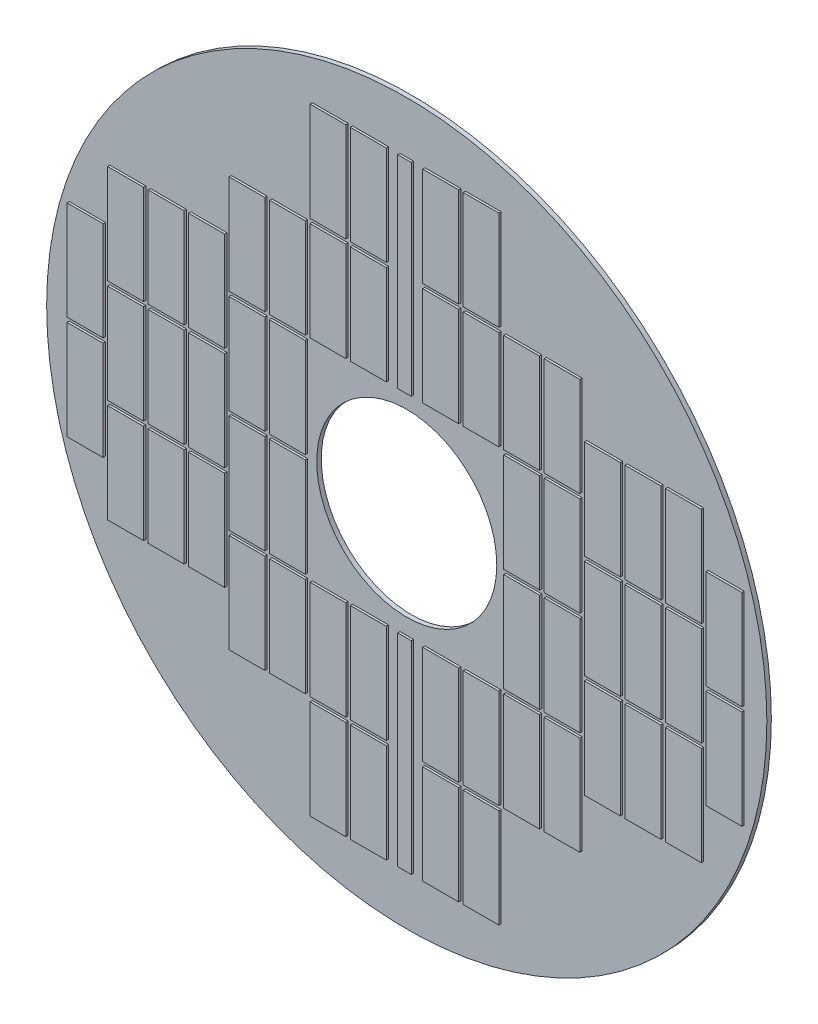
SolidWorks part; units mm, degrees
ref_plane "前视基准面" through (0, 0, 0) normal (0, 0, 1) x (1, 0, 0)
ref_plane "上视基准面" through (0, 0, 0) normal (0, 1, 0) x (1, 0, 0)
ref_plane "右视基准面" through (0, 0, 0) normal (1, 0, 0) x (0, 0, -1)
other "Configuration Table"
sketch "草图1" plane through (0, 0, 0) normal (0, 0, 1) x (1, 0, 0)
  line L0 (-1242.6073, 0) -> (1242.6073, 0) construction
  line L2 (0, -846.9805) -> (0, 846.9805) construction
  circle A0 centre (0, 0) radius 800
  circle A2 centre (0, 0) radius 200
  dimension "D1" = 1600
  dimension "D2" = 400
extrude "凸台-拉伸1" add sketch "草图1" along normal blind 10
sketch "草图2" plane through (0, 0, 0) normal (0, 0, 1) x (1, 0, 0)
  line L0 (669.6929, 225) -> (749.6929, 225)
  line L1 (669.6929, 225) -> (669.6929, 5)
  line L2 (669.6929, 5) -> (749.6929, 5)
  line L3 (749.6929, 225) -> (749.6929, 5)
  line L4 (579.6929, 110) -> (579.6929, -110)
  line L5 (579.6929, -110) -> (659.6929, -110)
  line L6 (579.6929, 110) -> (659.6929, 110)
  line L7 (659.6929, 110) -> (659.6929, -110)
  line L8 (489.6929, 110) -> (489.6929, -110)
  line L9 (489.6929, -110) -> (569.6929, -110)
  line L10 (569.6929, 110) -> (569.6929, -110)
  line L11 (489.6929, 110) -> (569.6929, 110)
  line L12 (399.6929, 110) -> (399.6929, -110)
  line L13 (399.6929, -110) -> (479.6929, -110)
  line L14 (479.6929, 110) -> (479.6929, -110)
  line L15 (399.6929, 110) -> (479.6929, 110)
  line L16 (579.6929, 340) -> (579.6929, 120)
  line L17 (579.6929, 120) -> (659.6929, 120)
  line L18 (659.6929, 340) -> (659.6929, 120)
  line L19 (579.6929, 340) -> (659.6929, 340)
  line L20 (489.6929, 340) -> (489.6929, 120)
  line L21 (489.6929, 120) -> (569.6929, 120)
  line L22 (569.6929, 340) -> (569.6929, 120)
  line L23 (489.6929, 340) -> (569.6929, 340)
  line L24 (399.6929, 340) -> (399.6929, 120)
  line L25 (399.6929, 120) -> (479.6929, 120)
  line L26 (479.6929, 340) -> (479.6929, 120)
  line L27 (399.6929, 340) -> (479.6929, 340)
  line L28 (310.4502, 225) -> (310.4502, 5)
  line L29 (389.6929, 225) -> (389.6929, 5)
  line L30 (310.4502, 5) -> (389.6929, 5)
  line L31 (310.4502, 225) -> (389.6929, 225)
  line L32 (220.4502, 225) -> (220.4502, 5)
  line L33 (300.4502, 225) -> (300.4502, 5)
  line L34 (220.4502, 5) -> (300.4502, 5)
  line L35 (220.4502, 225) -> (300.4502, 225)
  line L36 (310.4502, 455) -> (310.4502, 235)
  line L37 (310.4502, 235) -> (389.6929, 235)
  line L38 (389.6929, 455) -> (389.6929, 235)
  line L39 (310.4502, 455) -> (389.6929, 455)
  line L40 (220.4502, 455) -> (220.4502, 235)
  line L41 (220.4502, 235) -> (300.4502, 235)
  line L42 (300.4502, 455) -> (300.4502, 235)
  line L43 (220.4502, 455) -> (300.4502, 455)
  line L44 (130.4502, 455) -> (130.4502, 235)
  line L45 (130.4502, 235) -> (210.4502, 235)
  line L46 (210.4502, 455) -> (210.4502, 235)
  line L47 (130.4502, 455) -> (210.4502, 455)
  line L50 (299.6929, 455) -> (299.6929, 235)
  line L52 (40.4502, 455) -> (40.4502, 235)
  line L53 (40.4502, 235) -> (120.4502, 235)
  line L54 (120.4502, 455) -> (120.4502, 235)
  line L55 (40.4502, 455) -> (120.4502, 455)
  line L58 (209.6929, 455) -> (209.6929, 235)
  line L60 (130.4502, 685) -> (130.4502, 465)
  line L61 (130.4502, 465) -> (209.6929, 465)
  line L62 (209.6929, 685) -> (209.6929, 465)
  line L63 (130.4502, 685) -> (209.6929, 685)
  line L64 (40.4502, 685) -> (40.4502, 465)
  line L65 (40.4502, 465) -> (120.4502, 465)
  line L66 (120.4502, 685) -> (120.4502, 465)
  line L67 (40.4502, 685) -> (120.4502, 685)
  line L68 (130.4502, -685) -> (209.6929, -685)
  line L69 (209.6929, -685) -> (209.6929, -465)
  line L70 (130.4502, -465) -> (209.6929, -465)
  line L71 (130.4502, -685) -> (130.4502, -465)
  line L72 (40.4502, -685) -> (120.4502, -685)
  line L73 (120.4502, -685) -> (120.4502, -465)
  line L74 (40.4502, -465) -> (120.4502, -465)
  line L75 (40.4502, -685) -> (40.4502, -465)
  line L76 (40.4502, -455) -> (120.4502, -455)
  line L77 (120.4502, -455) -> (120.4502, -235)
  line L78 (40.4502, -235) -> (120.4502, -235)
  line L79 (40.4502, -455) -> (40.4502, -235)
  line L80 (130.4502, -455) -> (209.6929, -455)
  line L81 (209.6929, -455) -> (209.6929, -235)
  line L82 (130.4502, -235) -> (209.6929, -235)
  line L83 (130.4502, -455) -> (130.4502, -235)
  line L84 (220.4502, -455) -> (299.6929, -455)
  line L85 (299.6929, -455) -> (299.6929, -235)
  line L86 (220.4502, -235) -> (299.6929, -235)
  line L87 (220.4502, -455) -> (220.4502, -235)
  line L88 (310.4502, -455) -> (389.6929, -455)
  line L89 (389.6929, -455) -> (389.6929, -235)
  line L90 (310.4502, -235) -> (389.6929, -235)
  line L91 (310.4502, -455) -> (310.4502, -235)
  line L92 (669.6929, -5) -> (749.6929, -5)
  line L93 (749.6929, -225) -> (749.6929, -5)
  line L94 (669.6929, -225) -> (749.6929, -225)
  line L95 (669.6929, -225) -> (669.6929, -5)
  line L96 (579.6929, -340) -> (659.6929, -340)
  line L97 (659.6929, -340) -> (659.6929, -120)
  line L98 (579.6929, -120) -> (659.6929, -120)
  line L99 (579.6929, -340) -> (579.6929, -120)
  line L100 (489.6929, -340) -> (569.6929, -340)
  line L101 (569.6929, -340) -> (569.6929, -120)
  line L102 (489.6929, -120) -> (569.6929, -120)
  line L103 (489.6929, -340) -> (489.6929, -120)
  line L104 (399.6929, -340) -> (479.6929, -340)
  line L105 (479.6929, -340) -> (479.6929, -120)
  line L106 (399.6929, -120) -> (479.6929, -120)
  line L107 (399.6929, -340) -> (399.6929, -120)
  line L108 (310.4502, -225) -> (389.6929, -225)
  line L109 (389.6929, -225) -> (389.6929, -5)
  line L110 (310.4502, -5) -> (389.6929, -5)
  line L111 (310.4502, -225) -> (310.4502, -5)
  line L112 (220.4502, -225) -> (300.4502, -225)
  line L113 (300.4502, -225) -> (300.4502, -5)
  line L114 (220.4502, -5) -> (300.4502, -5)
  line L115 (220.4502, -225) -> (220.4502, -5)
  line L116 (-220.4502, -225) -> (-220.4502, -5)
  line L117 (-220.4502, -5) -> (-300.4502, -5)
  line L118 (-300.4502, -225) -> (-300.4502, -5)
  line L119 (-220.4502, -225) -> (-300.4502, -225)
  line L120 (-310.4502, -225) -> (-310.4502, -5)
  line L121 (-310.4502, -5) -> (-389.6929, -5)
  line L122 (-389.6929, -225) -> (-389.6929, -5)
  line L123 (-310.4502, -225) -> (-389.6929, -225)
  line L124 (-399.6929, -340) -> (-399.6929, -120)
  line L125 (-399.6929, -120) -> (-479.6929, -120)
  line L126 (-479.6929, -340) -> (-479.6929, -120)
  line L127 (-399.6929, -340) -> (-479.6929, -340)
  line L128 (-489.6929, -340) -> (-489.6929, -120)
  line L129 (-489.6929, -120) -> (-569.6929, -120)
  line L130 (-569.6929, -340) -> (-569.6929, -120)
  line L131 (-489.6929, -340) -> (-569.6929, -340)
  line L132 (-579.6929, -340) -> (-579.6929, -120)
  line L133 (-579.6929, -120) -> (-659.6929, -120)
  line L134 (-659.6929, -340) -> (-659.6929, -120)
  line L135 (-579.6929, -340) -> (-659.6929, -340)
  line L136 (-669.6929, -225) -> (-669.6929, -5)
  line L137 (-669.6929, -225) -> (-749.6929, -225)
  line L138 (-749.6929, -225) -> (-749.6929, -5)
  line L139 (-669.6929, -5) -> (-749.6929, -5)
  line L140 (-310.4502, -455) -> (-310.4502, -235)
  line L141 (-310.4502, -235) -> (-389.6929, -235)
  line L142 (-389.6929, -455) -> (-389.6929, -235)
  line L143 (-310.4502, -455) -> (-389.6929, -455)
  line L144 (-220.4502, -455) -> (-220.4502, -235)
  line L145 (-220.4502, -235) -> (-299.6929, -235)
  line L146 (-299.6929, -455) -> (-299.6929, -235)
  line L147 (-220.4502, -455) -> (-299.6929, -455)
  line L148 (-130.4502, -455) -> (-130.4502, -235)
  line L149 (-130.4502, -235) -> (-209.6929, -235)
  line L150 (-209.6929, -455) -> (-209.6929, -235)
  line L151 (-130.4502, -455) -> (-209.6929, -455)
  line L152 (-40.4502, -455) -> (-40.4502, -235)
  line L153 (-40.4502, -235) -> (-120.4502, -235)
  line L154 (-120.4502, -455) -> (-120.4502, -235)
  line L155 (-40.4502, -455) -> (-120.4502, -455)
  line L156 (-40.4502, -685) -> (-40.4502, -465)
  line L157 (-40.4502, -465) -> (-120.4502, -465)
  line L158 (-120.4502, -685) -> (-120.4502, -465)
  line L159 (-40.4502, -685) -> (-120.4502, -685)
  line L160 (-130.4502, -685) -> (-130.4502, -465)
  line L161 (-130.4502, -465) -> (-209.6929, -465)
  line L162 (-209.6929, -685) -> (-209.6929, -465)
  line L163 (-130.4502, -685) -> (-209.6929, -685)
  line L164 (-40.4502, 685) -> (-120.4502, 685)
  line L165 (-120.4502, 685) -> (-120.4502, 465)
  line L166 (-40.4502, 465) -> (-120.4502, 465)
  line L167 (-40.4502, 685) -> (-40.4502, 465)
  line L168 (-130.4502, 685) -> (-209.6929, 685)
  line L169 (-209.6929, 685) -> (-209.6929, 465)
  line L170 (-130.4502, 465) -> (-209.6929, 465)
  line L171 (-130.4502, 685) -> (-130.4502, 465)
  line L173 (-209.6929, 455) -> (-209.6929, 235)
  line L175 (-130.4502, 455) -> (-130.4502, 235)
  line L176 (-40.4502, 455) -> (-120.4502, 455)
  line L177 (-120.4502, 455) -> (-120.4502, 235)
  line L178 (-40.4502, 235) -> (-120.4502, 235)
  line L179 (-40.4502, 455) -> (-40.4502, 235)
  line L181 (-299.6929, 455) -> (-299.6929, 235)
  line L183 (-220.4502, 455) -> (-220.4502, 235)
  line L184 (-130.4502, 455) -> (-210.4502, 455)
  line L185 (-210.4502, 455) -> (-210.4502, 235)
  line L186 (-130.4502, 235) -> (-210.4502, 235)
  line L188 (-220.4502, 455) -> (-300.4502, 455)
  line L189 (-300.4502, 455) -> (-300.4502, 235)
  line L190 (-220.4502, 235) -> (-300.4502, 235)
  line L192 (-310.4502, 455) -> (-389.6929, 455)
  line L193 (-389.6929, 455) -> (-389.6929, 235)
  line L194 (-310.4502, 235) -> (-389.6929, 235)
  line L195 (-310.4502, 455) -> (-310.4502, 235)
  line L196 (-220.4502, 225) -> (-300.4502, 225)
  line L197 (-220.4502, 5) -> (-300.4502, 5)
  line L198 (-300.4502, 225) -> (-300.4502, 5)
  line L199 (-220.4502, 225) -> (-220.4502, 5)
  line L200 (-310.4502, 225) -> (-389.6929, 225)
  line L201 (-310.4502, 5) -> (-389.6929, 5)
  line L202 (-389.6929, 225) -> (-389.6929, 5)
  line L203 (-310.4502, 225) -> (-310.4502, 5)
  line L204 (-399.6929, 340) -> (-479.6929, 340)
  line L205 (-479.6929, 340) -> (-479.6929, 120)
  line L206 (-399.6929, 120) -> (-479.6929, 120)
  line L207 (-399.6929, 340) -> (-399.6929, 120)
  line L208 (-489.6929, 340) -> (-569.6929, 340)
  line L209 (-569.6929, 340) -> (-569.6929, 120)
  line L210 (-489.6929, 120) -> (-569.6929, 120)
  line L211 (-489.6929, 340) -> (-489.6929, 120)
  line L212 (-579.6929, 340) -> (-659.6929, 340)
  line L213 (-659.6929, 340) -> (-659.6929, 120)
  line L214 (-579.6929, 120) -> (-659.6929, 120)
  line L215 (-579.6929, 340) -> (-579.6929, 120)
  line L216 (-399.6929, 110) -> (-479.6929, 110)
  line L217 (-479.6929, 110) -> (-479.6929, -110)
  line L218 (-399.6929, -110) -> (-479.6929, -110)
  line L219 (-399.6929, 110) -> (-399.6929, -110)
  line L220 (-489.6929, 110) -> (-569.6929, 110)
  line L221 (-569.6929, 110) -> (-569.6929, -110)
  line L222 (-489.6929, -110) -> (-569.6929, -110)
  line L223 (-489.6929, 110) -> (-489.6929, -110)
  line L224 (-659.6929, 110) -> (-659.6929, -110)
  line L225 (-579.6929, 110) -> (-659.6929, 110)
  line L226 (-579.6929, -110) -> (-659.6929, -110)
  line L227 (-579.6929, 110) -> (-579.6929, -110)
  line L228 (-749.6929, 225) -> (-749.6929, 5)
  line L229 (-669.6929, 5) -> (-749.6929, 5)
  line L230 (-669.6929, 225) -> (-669.6929, 5)
  line L231 (-669.6929, 225) -> (-749.6929, 225)
  point P3 (0, 0)
  point P5 (0, 0)
  point P12 (659.6929, 0)
  point P233 (-659.6929, 0)
  dimension "D1" = 80
  dimension "D2" = 220
  dimension "D3" = 10
  dimension "D4" = 10
  dimension "D5" = 10
  dimension "D6" = 220
  dimension "D7" = 80
  dimension "D8" = 10
  dimension "D9" = 10
extrude "凸台-拉伸2" add sketch "草图2" along normal blind 15
sketch "草图3" plane through (0, 0, 0) normal (0, 0, 1) x (1, 0, 0)
  line L0 (-1504.4585, 0) -> (1504.4585, 0) construction
  line L1 (0, -930.669) -> (0, 930.669) construction
  line L2 (40.4502, 685) -> (120.4502, 685) construction
  line L3 (-15, 685) -> (15, 685)
  line L4 (-15, 685) -> (-15, 235)
  line L5 (-15, 235) -> (15, 235)
  line L6 (15, 685) -> (15, 235)
  line L7 (-15, 685) -> (15, 235) construction
  line L8 (-15, 235) -> (15, 685) construction
  line L9 (120.4502, 235) -> (40.4502, 235) construction
  line L12 (-15, -235) -> (15, -235)
  line L13 (15, -685) -> (15, -235)
  line L14 (-15, -685) -> (15, -685)
  line L15 (-15, -685) -> (-15, -235)
  point P0 (0, 460)
  point P5 (0, 0)
  point P9 (0, 0)
  point P18 (0, 0)
  dimension "D1" = 30
extrude "凸台-拉伸3" add sketch "草图3" along normal blind 15
